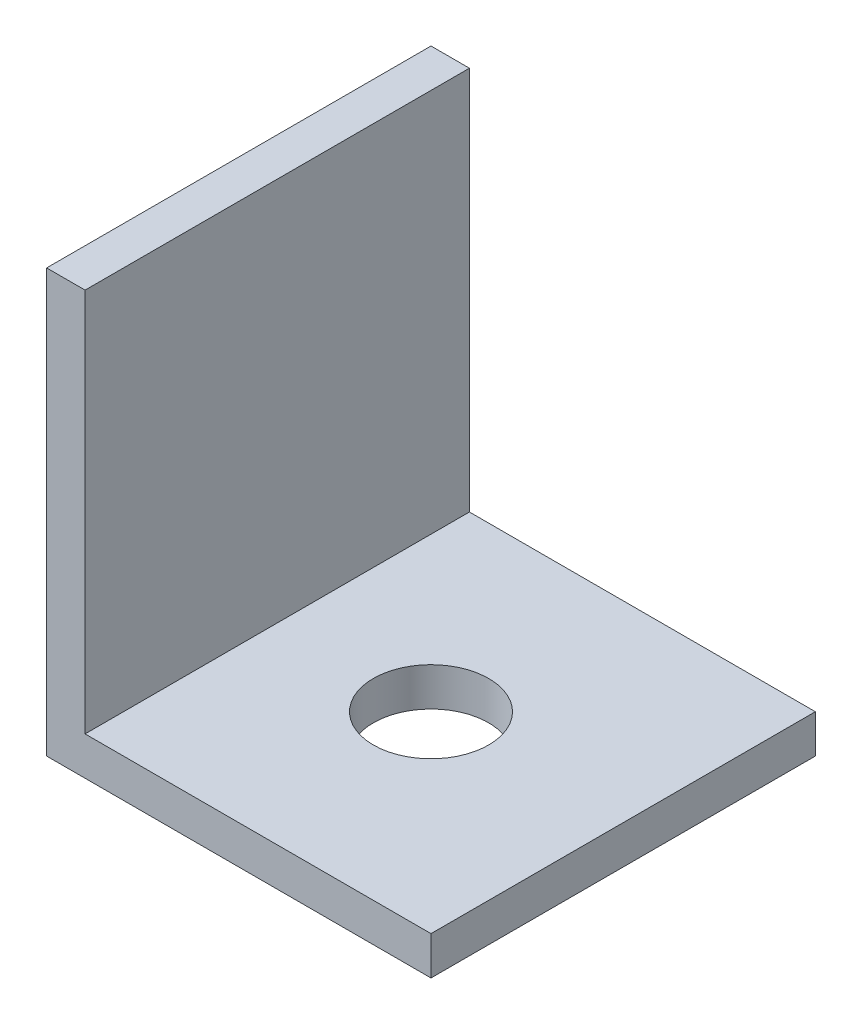
SolidWorks part; units mm, degrees
ref_plane "正面" through (0, 0, 0) normal (0, 0, 1) x (1, 0, 0)
ref_plane "平面" through (0, 0, 0) normal (0, 1, 0) x (1, 0, 0)
ref_plane "右側面" through (0, 0, 0) normal (1, 0, 0) x (0, 0, -1)
sketch "ｽｹｯﾁ2" plane through (0, 0, 0) normal (0, 1, 0) x (1, 0, 0)
  line L1 (-10, 10) -> (10, 10)
  line L2 (-10, 10) -> (-10, -10)
  line L3 (-10, -10) -> (10, -10)
  line L4 (10, 10) -> (10, -10)
  line L5 (-10, 10) -> (10, -10) construction
  line L6 (-10, -10) -> (10, 10) construction
  circle A0 centre (0, 0) radius 3
  point P0 (0, 0)
  dimension "D3" = 6
  dimension "D1" = 20
  dimension "D2" = 20
extrude "ﾎﾞｽ - 押し出し1" add sketch "ｽｹｯﾁ2" along normal blind 2
sketch "ｽｹｯﾁ3" plane through (0, 2, 0) normal (0, 1, 0) x (1, 0, 0)
  line L0 (-10, -10) -> (10, -10) construction
  line L1 (-10, 10) -> (-8, 10)
  line L2 (-10, 10) -> (-10, -10)
  line L3 (-10, -10) -> (-8, -10)
  line L4 (-8, 10) -> (-8, -10)
  dimension "D1" = 2
extrude "ﾎﾞｽ - 押し出し2" add sketch "ｽｹｯﾁ3" along normal blind 20
